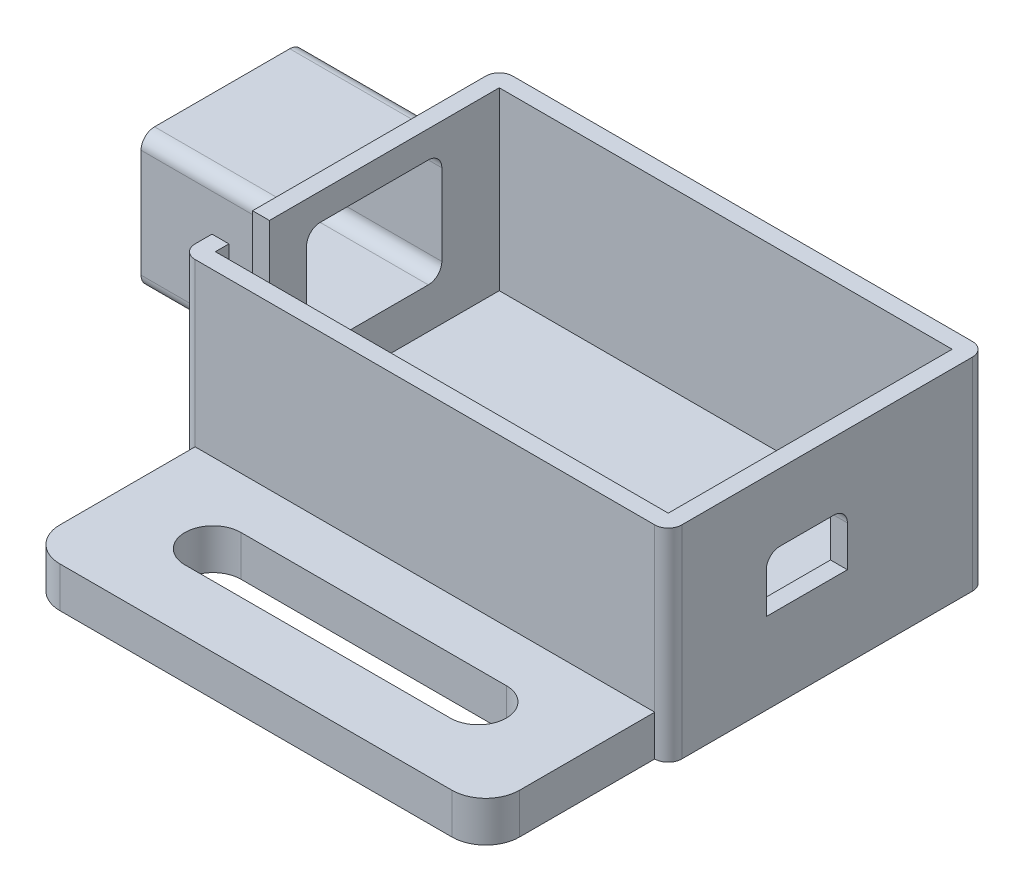
SolidWorks part; units mm, degrees
ref_plane "Front Plane" through (0, 0, 0) normal (0, 0, 1) x (1, 0, 0)
ref_plane "Top Plane" through (0, 0, 0) normal (0, 1, 0) x (1, 0, 0)
ref_plane "Right Plane" through (0, 0, 0) normal (1, 0, 0) x (0, 0, -1)
sketch "Sketch1" plane through (0, 0, 0) normal (0, 1, 0) x (1, 0, 0)
  line L0 (-10.5, -10.5) -> (-10.5, 36.5)
  line L1 (0, 0) -> (51, 0) construction
  line L2 (0, 0) -> (0, 26) construction
  line L3 (0, 26) -> (51, 26) construction
  line L4 (51, 0) -> (51, 26) construction
  line L5 (-10.5, 36.5) -> (61.5, 36.5)
  line L6 (61.5, -10.5) -> (61.5, 36.5)
  line L7 (-10.5, -10.5) -> (61.5, -10.5)
  line L8 (25.5, 36.5) -> (25.5, -10.5) construction
  line L9 (-10.5, 13) -> (61.5, 13) construction
  dimension "D1" = 51
  dimension "D2" = 26
  dimension "D3" = 10.5
extrude "Boss-Extrude1" add sketch "Sketch1" along normal blind 4
sketch "Sketch2" plane through (0, 4, 0) normal (0, 1, 0) x (1, 0, 0)
  line L0 (-3, 13) -> (54, 13) construction
  line L1 (25.5, 29) -> (25.5, -3) construction
  line L8 (-3, 29) -> (-3, -3)
  line L9 (54, 29) -> (-3, 29)
  line L10 (54, -3) -> (54, 29)
  line L11 (-3, -3) -> (54, -3)
  line L12 (-3, 29) -> (-3, -3) construction
  line L13 (54, 29) -> (-3, 29) construction
  line L14 (54, -3) -> (54, 29) construction
  line L15 (-3, -3) -> (54, -3) construction
  circle A4 centre (-1.2, 27.2) radius 0.9
  circle A5 centre (-1.2, -1.2) radius 0.9
  circle A6 centre (52.2, -1.2) radius 0.9
  circle A7 centre (52.2, 27.2) radius 0.9
  dimension "D2" = 1.8
  dimension "D3" = 1.8
  dimension "D4" = 1.8
  dimension "D1" = 7.5
sketch "Sketch3" plane through (0, 4, 0) normal (0, 1, 0) x (1, 0, 0)
  line L0 (61.5, -10.5) -> (61.5, 36.5) construction
  line L1 (-10.5, -10.5) -> (61.5, -10.5) construction
  line L2 (61.5, 36.5) -> (-10.5, 36.5) construction
  line L3 (-10.5, 36.5) -> (-10.5, -10.5) construction
  line L4 (61.5, -10.5) -> (61.5, 36.5)
  line L5 (-10.5, -10.5) -> (61.5, -10.5)
  line L6 (61.5, 36.5) -> (-10.5, 36.5)
  line L7 (-10.5, 36.5) -> (-10.5, -10.5)
  line L8 (59, -8) -> (59, 34)
  line L9 (59, 34) -> (-8, 34)
  line L10 (-8, 34) -> (-8, -8)
  line L11 (-8, -8) -> (59, -8)
  dimension "D1" = 2.5
extrude "Boss-Extrude3" add sketch "Sketch3" along normal blind 26
extrude "Boss-Extrude4" [suppressed] add sketch "Sketch2" along normal blind 16
sketch "Sketch4" [suppressed] plane through (0, 4, 0) normal (0, 1, 0) x (1, 0, 0)
  line L0 (25.5, 34) -> (25.5, -8) construction
  line L1 (59, 34) -> (-8, 34) construction
  line L2 (-8, -8) -> (59, -8) construction
  line L3 (-8, 13) -> (59, 13) construction
  line L4 (-8, 34) -> (-8, -8) construction
  line L5 (59, -8) -> (59, 34) construction
  circle A0 centre (-1.2, 27.2) radius 2
  circle A1 centre (-1.2, -1.2) radius 2
  circle A2 centre (52.2, -1.2) radius 2
  circle A3 centre (52.2, 27.2) radius 2
  dimension "D1" = 4
extrude "Boss-Extrude5" [suppressed] add sketch "Sketch4" along normal blind 6
sketch "Sketch5" plane through (61.5, 0, 0) normal (1, 0, 0) x (0, 0, -1)
  line L1 (-8, 30) -> (-8, 4) construction
  line L7 (4, 20) -> (16, 20)
  line L8 (4, 20) -> (4, 12)
  line L9 (4, 12) -> (16, 12)
  line L10 (16, 20) -> (16, 12)
  line L11 (-8, 4) -> (34, 4) construction
  line L12 (-8, 30) -> (-8, 4) construction
  line L13 (-8, 4) -> (34, 4) construction
  dimension "D1" = 8
  dimension "D2" = 12
  dimension "D3" = 8
  dimension "D4" = 12
extrude "Cut-Extrude1" cut sketch "Sketch5" against normal blind 6
fillet "Fillet2" radius 2 4 edges at (-10.5, 15, 10.5) (-10.5, 15, -36.5) (61.5, 15, -36.5) (61.5, 15, 10.5)
fillet "Fillet3" radius 2 2 edges at (60.25, 20, -4) (60.25, 20, -16)
sketch "Sketch6" plane through (0, 0, 10.5) normal (0, 0, 1) x (1, 0, 0)
  line L0 (-8, 4) -> (59, 4) construction
  line L1 (59, 30) -> (59, 4) construction
  line L2 (-8, 4) -> (59, 4) construction
  line L3 (59, 30) -> (59, 4) construction
  line L5 (28, 24) -> (44, 24)
  line L6 (28, 24) -> (28, 15)
  line L7 (28, 15) -> (44, 15)
  line L8 (44, 24) -> (44, 15)
  dimension "D1" = 16
  dimension "D2" = 9
  dimension "D3" = 15
  dimension "D4" = 11
extrude "Cut-Extrude2" [suppressed] cut sketch "Sketch6" against normal blind 6 contours L7 L8 L5 L6
sketch "Sketch8" [suppressed] plane through (-10.5, 0, 0) normal (-1, 0, 0) x (0, 0, 1)
  line L0 (-34.5, 28) -> (-34.5, 0) construction
  line L1 (-22.5, 20) -> (-10.5, 20)
  line L2 (-22.5, 20) -> (-22.5, 12)
  line L3 (-22.5, 12) -> (-10.5, 12)
  line L4 (-10.5, 20) -> (-10.5, 12)
  line L6 (-34, 4) -> (8, 4) construction
  line L7 (-34, 4) -> (8, 4) construction
  dimension "D1" = 12
  dimension "D2" = 8
  dimension "D3" = 8
  dimension "D4" = 12
sketch "Sketch11" plane through (-10.5, 0, 0) normal (-1, 0, 0) x (0, 0, 1)
  line L0 (-34.5, 30) -> (8.5, 30) construction
  line L1 (-27.5, 28) -> (-3.5, 28)
  line L2 (-27.5, 28) -> (-27.5, 8)
  line L3 (-27.5, 8) -> (-3.5, 8)
  line L4 (-3.5, 28) -> (-3.5, 8)
  line L5 (-34.5, 30) -> (-34.5, 0) construction
  dimension "D1" = 24
  dimension "D2" = 20
  dimension "D3" = 2
  dimension "D4" = 7
extrude "Boss-Extrude7" add sketch "Sketch11" along normal blind 20
sketch "Sketch12" plane through (-8, 0, 0) normal (1, 0, 0) x (0, 0, -1)
  line L0 (27.5, 8) -> (3.5, 8) construction
  line L1 (3.5, 28) -> (27.5, 28) construction
  line L2 (3.5, 8) -> (3.5, 28) construction
  line L3 (27.5, 28) -> (27.5, 8) construction
  line L4 (27.5, 8) -> (3.5, 8) construction
  line L5 (3.5, 28) -> (27.5, 28) construction
  line L6 (3.5, 8) -> (3.5, 28) construction
  line L7 (27.5, 28) -> (27.5, 8) construction
  line L8 (5.5, 10) -> (5.5, 26)
  line L9 (5.5, 26) -> (25.5, 26)
  line L10 (25.5, 26) -> (25.5, 10)
  line L11 (25.5, 10) -> (5.5, 10)
  dimension "D1" = 2
extrude "Cut-Extrude4" cut sketch "Sketch12" against normal blind 20 contours L8 L9 L10 L11
sketch "Sketch13" plane through (-30.5, 0, 0) normal (-1, 0, 0) x (0, 0, 1)
  line L0 (-3.5, 28) -> (-27.5, 28) construction
  line L1 (-23, 22.5) -> (-8, 22.5)
  line L2 (-23, 22.5) -> (-23, 13.5)
  line L3 (-23, 13.5) -> (-8, 13.5)
  line L4 (-8, 22.5) -> (-8, 13.5)
  line L7 (-3.5, 8) -> (-3.5, 28) construction
  dimension "D1" = 15
  dimension "D2" = 9
  dimension "D3" = 5.5
  dimension "D4" = 4.5
extrude "Cut-Extrude5" cut sketch "Sketch13" against normal blind 20
fillet "Fillet4" radius 2 4 edges at (-18, 10, -25.5) (-18, 26, -25.5) (-18, 26, -5.5) (-18, 10, -5.5)
fillet "Fillet5" radius 2 4 edges at (-20.5, 8, -3.5) (-20.5, 28, -3.5) (-20.5, 8, -27.5) (-20.5, 28, -27.5)
sketch "Sketch14" plane through (-10.5, 0, 0) normal (-1, 0, 0) x (0, 0, 1)
  line L0 (-34.5, 0) -> (8.5, 0) construction
  line L1 (0, 37) -> (6, 37)
  line L2 (0, 37) -> (0, 12)
  line L3 (0, 12) -> (6, 12)
  line L4 (6, 37) -> (6, 12)
  dimension "D1" = 6
  dimension "D2" = 25
  dimension "D3" = 12
extrude "Cut-Extrude6" cut sketch "Sketch14" against normal blind 5
fillet "Fillet6" radius 2 2 edges at (-9.25, 12, 6) (-9.25, 12, 0)
sketch "Sketch15" plane through (0, 0, 10.5) normal (0, 0, 1) x (1, 0, 0)
  line L0 (-8.5, 0) -> (59.5, 0) construction
  line L1 (-8.5, 0) -> (59.5, 0)
  line L2 (-8.5, 6) -> (59.5, 6)
  line L3 (-8.5, 6) -> (-8.5, 0)
  line L4 (59.5, 6) -> (59.5, 0)
  dimension "D1" = 6
extrude "Boss-Extrude8" add sketch "Sketch15" along normal blind 25
fillet "Fillet7" radius 5 2 edges at (59.5, 3, 35.5) (-8.5, 3, 35.5)
sketch "Sketch16" plane through (0, 6, 0) normal (0, 1, 0) x (1, 0, 0)
  line L0 (59.5, -10.5) -> (-8.5, -10.5) construction
  line L1 (54.5, -35.5) -> (-3.5, -35.5) construction
  line L2 (59.5, -10.5) -> (-8.5, -10.5) construction
  line L3 (54.5, -35.5) -> (-3.5, -35.5) construction
  line L4 (25.5, -35.5) -> (25.5, -10.5) construction
  line L5 (-8.5, -30.5) -> (-8.5, -10.5) construction
  line L6 (5.87, -22.2289) -> (45.13, -22.2289) construction
  line L7 (5.87, -18.0789) -> (45.13, -18.0789)
  line L8 (5.87, -26.3789) -> (45.13, -26.3789)
  arc A0 (5.87, -18.0789) -> (5.87, -26.3789) centre (5.87, -22.2289) ccw
  arc A1 (45.13, -26.3789) -> (45.13, -18.0789) centre (45.13, -22.2289) ccw
  point P10 (25.5, -22.2289)
  dimension "D1" = 8.3
  dimension "D2" = 34
extrude "Cut-Extrude7" cut sketch "Sketch16" against normal blind 25 contours L8 A1 L7 A0
